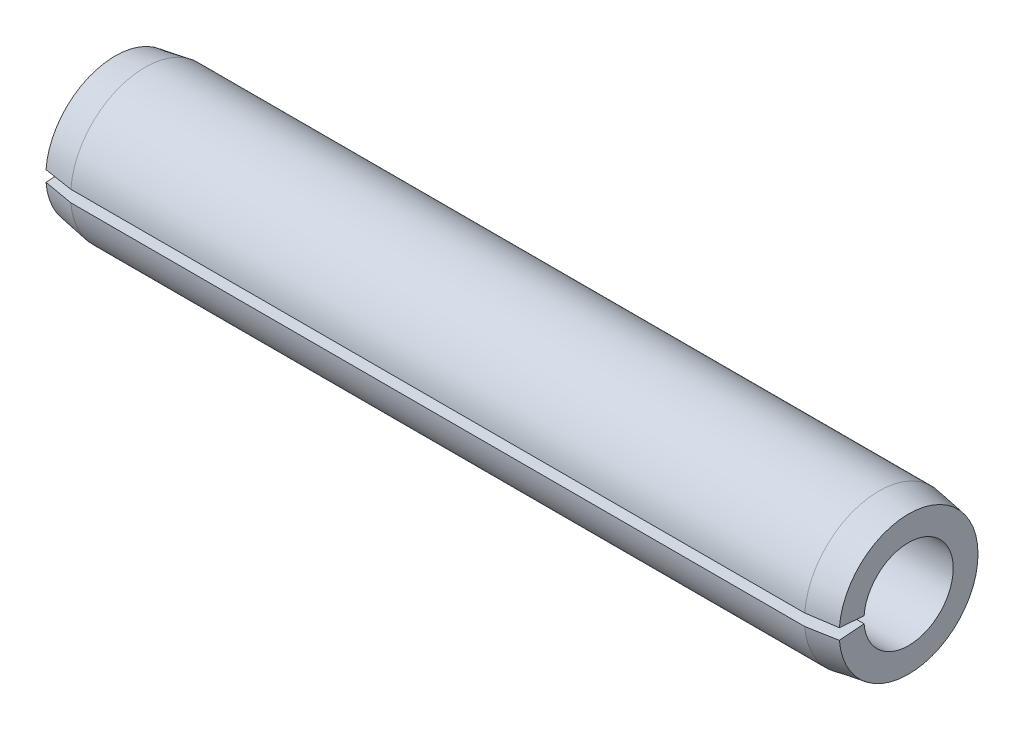
SolidWorks part; units mm, degrees
ref_plane "Plane1" through (0, 0, 0) normal (0, 0, 1) x (1, 0, 0)
ref_plane "Plane2" through (0, 0, 0) normal (0, 1, 0) x (1, 0, 0)
ref_plane "Plane3" through (0, 0, 0) normal (1, 0, 0) x (0, 0, -1)
sketch "Sketch1" plane through (0, 0, 0) normal (0, 0, 1) x (1, 0, 0)
  line L0 (-9.525, 0) -> (111.125, 0) construction
  line L1 (0, 5.715) -> (101.6, 5.715)
  line L2 (101.6, 5.715) -> (101.6, 8.89)
  line L3 (101.6, 8.89) -> (97.79, 9.525)
  line L4 (97.79, 9.525) -> (3.81, 9.525)
  line L5 (3.81, 9.525) -> (0, 8.89)
  line L7 (0, 8.89) -> (0, 5.715)
  dimension "Diameter" = 19.05
  dimension "Thickness" = 3.81
  dimension "Length" = 101.6
  dimension "Bottom_ch_len" = 3.81
  dimension "Bottom_ch_dia" = 17.78
  dimension "Top_ch_dia" = 17.78
  dimension "Top_ch_len" = 3.81
revolve "Base-Revolve" add sketch "Sketch1" angle 360 about L0
sketch "Sketch2" plane through (0, 0, 0) normal (-1, 0, 0) x (0, -1, 0)
  line L0 (0, 0) -> (0.7623, 9.6856)
  line L1 (0, -3.175) -> (0, 12.7) construction
  line L2 (0, 0) -> (-0.7623, 9.6856)
  arc A0 (0.7623, 9.6856) -> (-0.7623, 9.6856) centre (0, 0) ccw
  dimension "Gap_ang" = 9
  dimension "D1" = 9.7155
extrude "Gap" cut sketch "Sketch2" against normal through all
equation "\"D1@Sketch2\" = \"Diameter@Sketch1\" * 0.51"
equation "' \"Bottom_ch_dia@Sketch1\" = \"Diameter@Sketch1\" -  ( \"Thickness@Sketch1\" / 2 ) "
equation "' \"Bottom_ch_dia@Sketch1\" = \"Diameter@Sketch1\" -  ( \"Thickness@Sketch1\" / 2 )"
equation "' \"Top_ch_dia@Sketch1\" = \"Bottom_ch_dia@Sketch1\""
equation "' \"Top_ch_len@Sketch1\" = \"Bottom_ch_len@Sketch1\""
